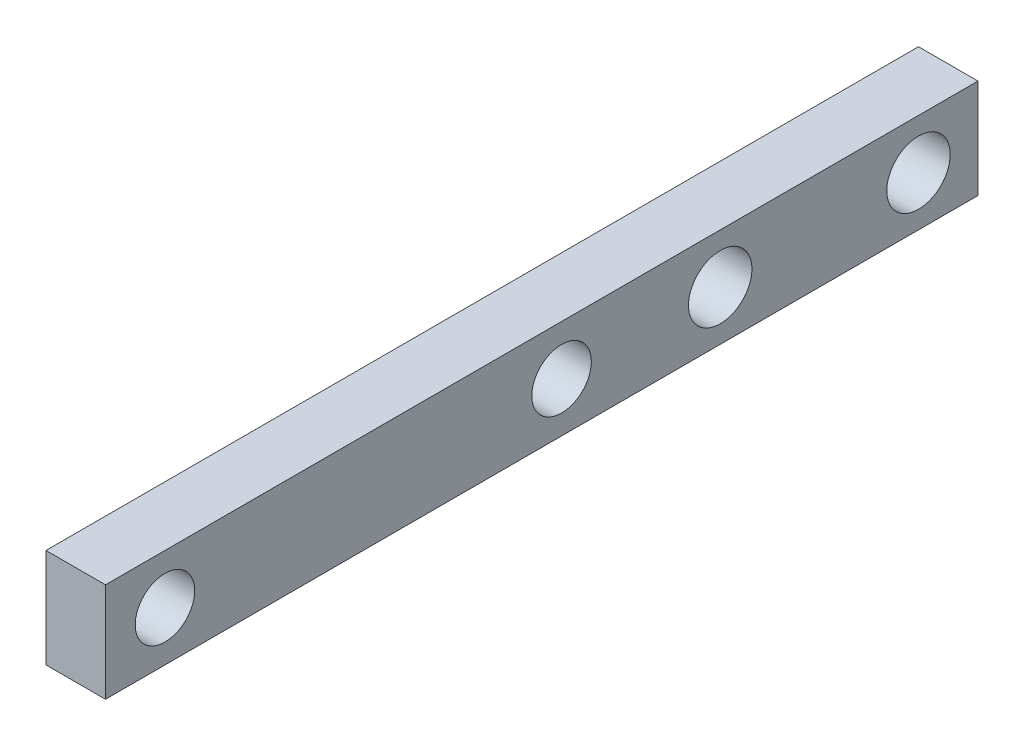
SolidWorks part; units mm, degrees
ref_plane "Front Plane" through (0, 0, 0) normal (0, 0, 1) x (1, 0, 0)
ref_plane "Top Plane" through (0, 0, 0) normal (0, 1, 0) x (1, 0, 0)
ref_plane "Right Plane" through (0, 0, 0) normal (1, 0, 0) x (0, 0, -1)
sketch "Sketch2" plane through (0, 0, 0) normal (1, 0, 0) x (0, 0, -1)
  line L1 (-22, -2.5) -> (22, -2.5)
  line L2 (-22, -2.5) -> (-22, 2.5)
  line L3 (-22, 2.5) -> (22, 2.5)
  line L4 (22, -2.5) -> (22, 2.5)
  line L5 (0, 2.5) -> (0, -2.5) construction
  line L6 (-22, 0) -> (22, 0) construction
  circle A0 centre (19, 0) radius 1.6
  circle A1 centre (9, 0) radius 1.6
  circle A2 centre (1, 0) radius 1.5
  circle A3 centre (-19, 0) radius 1.5
  point P0 (0, 0)
  dimension "D3" = 3.2
  dimension "D5" = 3.2
  dimension "D7" = 3
  dimension "D9" = 3
  dimension "D1" = 44
  dimension "D2" = 5
  dimension "D4" = 3
  dimension "D6" = 10
  dimension "D8" = 8
  dimension "D10" = 20
extrude "Boss-Extrude1" add sketch "Sketch2" along normal blind 3
